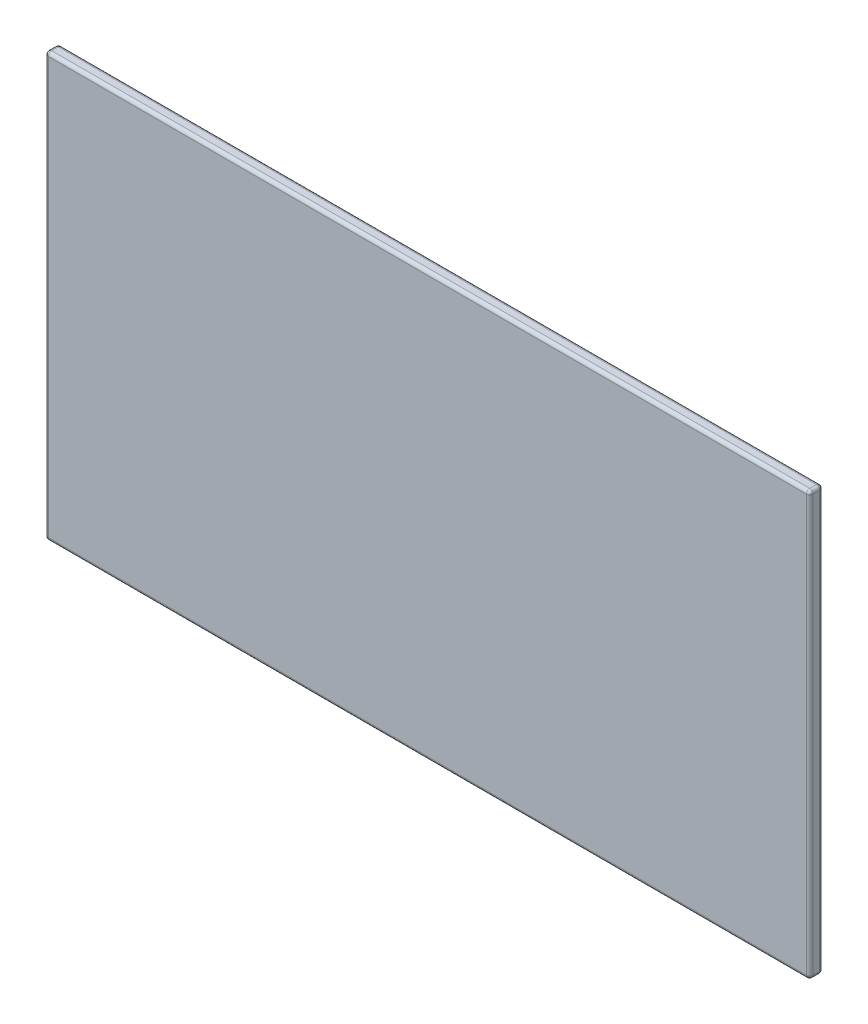
SolidWorks part; units mm, degrees
ref_plane "Front Plane" through (0, 0, 0) normal (0, 0, 1) x (1, 0, 0)
ref_plane "Top Plane" through (0, 0, 0) normal (0, 1, 0) x (1, 0, 0)
ref_plane "Right Plane" through (0, 0, 0) normal (1, 0, 0) x (0, 0, -1)
sketch "Sketch1" plane through (0, 0, 0) normal (0, 0, 1) x (1, 0, 0)
  line L1 (-57.35, -31.75) -> (57.35, -31.75)
  line L2 (-57.35, -31.75) -> (-57.35, 31.75)
  line L3 (-57.35, 31.75) -> (57.35, 31.75)
  line L4 (57.35, -31.75) -> (57.35, 31.75)
  line L5 (-57.35, -31.75) -> (57.35, 31.75) construction
  line L6 (-57.35, 31.75) -> (57.35, -31.75) construction
  point P0 (0, 0)
  dimension "D1" = 114.7
  dimension "D2" = 63.5
extrude "Boss-Extrude1" add sketch "Sketch1" along normal blind 2
fillet "Fillet1" radius 0.5 12 edges at (0, -31.75, 2) (0, -31.75, 0) (-57.35, 0, 2) (-57.35, -31.75, 1) (-57.35, 0, 0) (0, 31.75, 2) (-57.35, 31.75, 1) (0, 31.75, 0) (57.35, -31.75, 1) (57.35, 0, 2) (57.35, 31.75, 1) (57.35, 0, 0)
